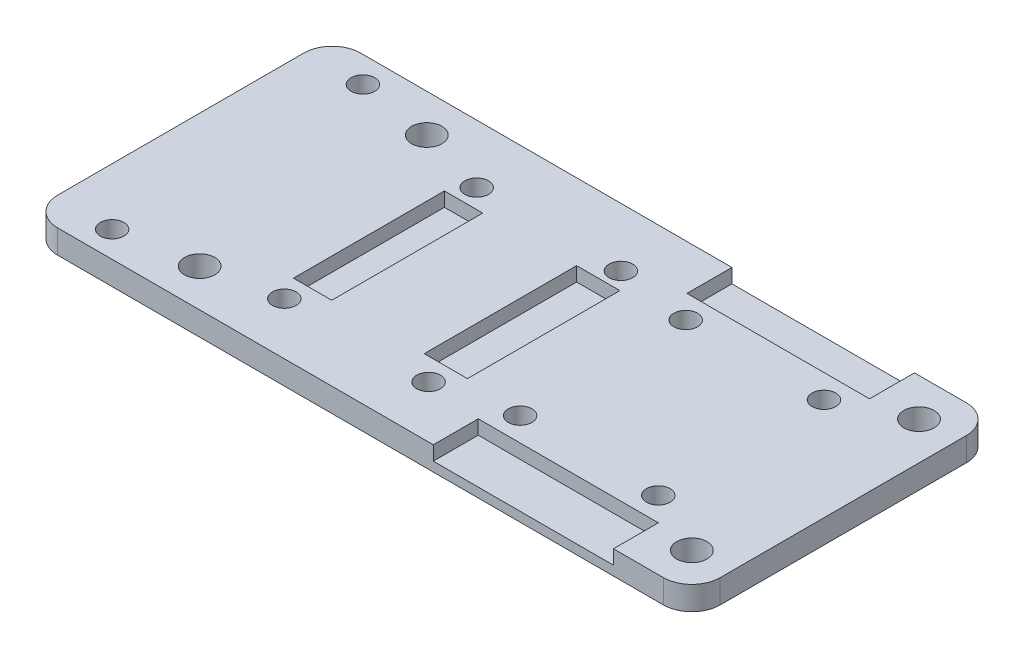
SolidWorks part; units mm, degrees
ref_plane "Front Plane" through (0, 0, 0) normal (0, 0, 1) x (1, 0, 0)
ref_plane "Top Plane" through (0, 0, 0) normal (0, 1, 0) x (1, 0, 0)
ref_plane "Right Plane" through (0, 0, 0) normal (1, 0, 0) x (0, 0, -1)
sketch "Sketch1" plane through (0, 0, 0) normal (0, 1, 0) x (1, 0, 0)
  line L0 (-3.3147, 0) -> (3.3147, 0) construction
  line L1 (-30, -16) -> (30, -16)
  line L3 (-30, 16) -> (30, 16)
  line L4 (30, -16) -> (30, 16)
  line L5 (-26, 12) -> (26, 12) construction
  line L6 (-26, 12) -> (-26, -12) construction
  line L7 (-26, -12) -> (26, -12) construction
  line L8 (26, 12) -> (26, -12) construction
  line L9 (-18.5547, 9.82) -> (-3.3147, 9.82) construction
  line L10 (-18.5547, 9.82) -> (-18.5547, -10.5) construction
  line L11 (-18.5547, -10.5) -> (-3.3147, -10.5) construction
  line L12 (-3.3147, 9.82) -> (-3.3147, -10.5) construction
  line L13 (4.6062, 8.75) -> (19.2062, 8.75) construction
  line L14 (4.6062, 8.75) -> (4.6062, -8.75) construction
  line L15 (4.6062, -8.75) -> (19.2062, -8.75) construction
  line L16 (19.2062, 8.75) -> (19.2062, -8.75) construction
  line L17 (-30, 16) -> (-40, 16)
  line L18 (-40, 16) -> (-40, -16)
  line L19 (-40, -16) -> (-30, -16)
  line L20 (-34, 16) -> (-34, -16) construction
  circle A0 centre (-26, 12) radius 1.6
  circle A1 centre (26, 12) radius 1.6
  circle A2 centre (26, -12) radius 1.6
  circle A3 centre (-26, -12) radius 1.6
  circle A4 centre (-18.5547, 9.82) radius 1.25
  circle A5 centre (-3.3147, 9.82) radius 1.25
  circle A6 centre (-3.3147, -10.5) radius 1.25
  circle A7 centre (-18.5547, -10.5) radius 1.25
  circle A8 centre (4.6062, 8.75) radius 1.25
  circle A9 centre (19.2062, 8.75) radius 1.25
  circle A10 centre (19.2062, -8.75) radius 1.25
  circle A11 centre (4.6062, -8.75) radius 1.25
  circle A12 centre (-34, 13.25) radius 1.25
  circle A13 centre (-34, -13.25) radius 1.25
  point P0 (0, 0)
  point P15 (-26, 0)
  point P16 (26, 0)
  point P17 (30, 0)
  point P18 (0, -12)
  point P19 (0, -16)
  point P20 (0, 12)
  point P21 (0, 16)
  point P40 (0, 0)
  point P51 (4.6062, 0)
  dimension "D3" = 3.2
  dimension "D6" = 2.5
  dimension "D11" = 26.5
  dimension "D1" = 32
  dimension "D2" = 60
  dimension "D4" = 4
  dimension "D5" = 4
  dimension "D7" = 5.5
  dimension "D8" = 15.24
  dimension "20" = 20.32
  dimension "D10" = 10
  dimension "D12" = 2.75
  dimension "D13" = 6
  dimension "D14" = 14.6
  dimension "D15" = 17.5
extrude "Boss-Extrude1" add sketch "Sketch1" along normal blind 2.5
sketch "Sketch4" plane through (0, 2.5, 0) normal (0, 1, 0) x (1, 0, 0)
  line L0 (-3.3147, 9.82) -> (-3.3147, -10.5) construction
  line L1 (-18.5547, 9.82) -> (-18.5547, -10.5) construction
  line L2 (30, 16) -> (-40, 16) construction
  line L3 (-19.9501, 7.8114) -> (-15.9036, 7.8114)
  line L4 (-19.9501, 7.8114) -> (-19.9501, -8.1434)
  line L5 (-19.9501, -8.1434) -> (-15.9036, -8.1434)
  line L6 (-15.9036, 7.8114) -> (-15.9036, -8.1434)
  line L7 (-6.1315, 7.9609) -> (-1.5615, 7.9609)
  line L8 (-6.1315, 7.9609) -> (-6.1315, -8.1434)
  line L9 (-6.1315, -8.1434) -> (-1.5615, -8.1434)
  line L10 (-1.5615, 7.9609) -> (-1.5615, -8.1434)
  line L11 (2.2355, 16) -> (21.5242, 16)
  line L12 (2.2355, 16) -> (2.2355, 11.25)
  line L13 (2.2355, 11.25) -> (21.5242, 11.25)
  line L14 (21.5242, 16) -> (21.5242, 11.25)
  line L15 (-40, -16) -> (30, -16) construction
  line L16 (2.6825, -11.25) -> (21.7158, -11.25)
  line L17 (2.6825, -11.25) -> (2.6825, -16)
  line L18 (2.6825, -16) -> (21.7158, -16)
  line L19 (21.7158, -11.25) -> (21.7158, -16)
  circle A0 centre (4.6062, 8.75) radius 1.25 construction
  dimension "D1" = 2.5
extrude "Cut-Extrude2" cut sketch "Sketch4" against normal blind 1.5
fillet "Fillet1" radius 3 4 edges at (30, 1.25, -16) (30, 1.25, 16) (-40, 1.25, 16) (-40, 1.25, -16)
